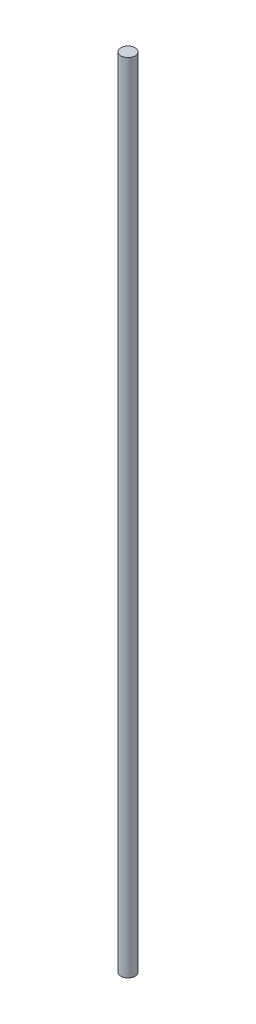
SolidWorks part; units mm, degrees
ref_plane "Front Plane" through (0, 0, 0) normal (0, 0, 1) x (1, 0, 0)
ref_plane "Top Plane" through (0, 0, 0) normal (0, 1, 0) x (1, 0, 0)
ref_plane "Right Plane" through (0, 0, 0) normal (1, 0, 0) x (0, 0, -1)
sketch "Sketch1" plane through (0, 0, 0) normal (0, 1, 0) x (1, 0, 0)
  circle A0 centre (0, 0) radius 4
  dimension "D1" = 8
extrude "Boss-Extrude1" add sketch "Sketch1" along normal blind 450
